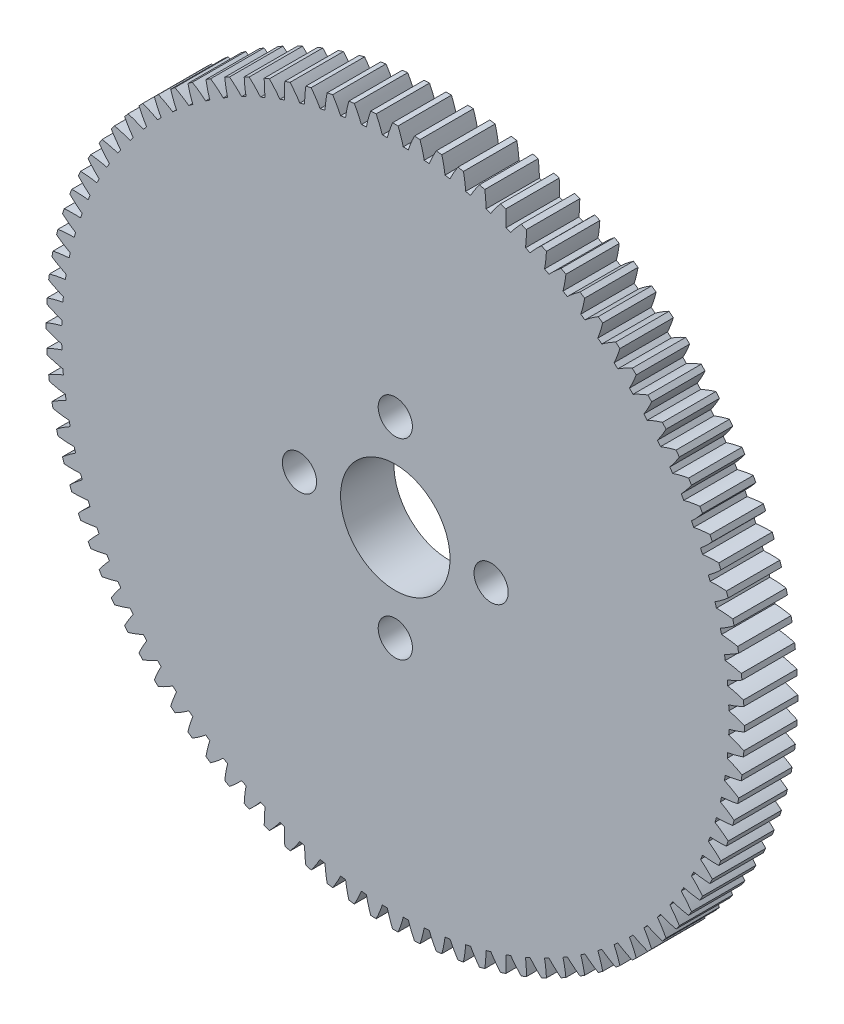
SolidWorks part; units mm, degrees
material "ABS"
ref_plane "Front Plane" through (0, 0, 0) normal (0, 0, 1) x (1, 0, 0)
ref_plane "Top Plane" through (0, 0, 0) normal (0, 1, 0) x (1, 0, 0)
ref_plane "Right Plane" through (0, 0, 0) normal (1, 0, 0) x (0, 0, -1)
ref_plane "Plane1" through (0, 0, 4) normal (0, 0, 1) x (1, 0, 0)
sketch "Sketch1" plane through (0, 0, 4) normal (0, 0, 1) x (1, 0, 0)
  line L0 (25.4992, -0.2018) -> (25.4992, 0.2018)
  line L1 (25.4616, 1.3997) -> (25.4362, 1.8025)
  line L2 (25.3234, 2.9957) -> (25.2728, 3.3961)
  line L3 (25.0854, 4.5799) -> (25.0097, 4.9763)
  line L4 (24.7483, 6.1459) -> (24.6479, 6.5369)
  line L5 (24.3135, 7.6878) -> (24.1888, 8.0716)
  line L6 (23.7828, 9.1993) -> (23.6343, 9.5745)
  line L7 (23.1583, 10.6744) -> (22.9864, 11.0396)
  line L8 (22.4423, 12.1075) -> (22.2479, 12.4612)
  line L9 (21.6378, 13.4928) -> (21.4216, 13.8335)
  line L10 (20.7479, 14.8248) -> (20.5107, 15.1513)
  line L11 (19.7761, 16.0983) -> (19.5188, 16.4093)
  line L12 (18.7263, 17.3083) -> (18.45, 17.6025)
  line L13 (17.6025, 18.45) -> (17.3083, 18.7263)
  line L14 (16.4093, 19.5188) -> (16.0983, 19.7761)
  line L15 (15.1513, 20.5107) -> (14.8248, 20.7479)
  line L16 (13.8335, 21.4216) -> (13.4928, 21.6378)
  line L17 (12.4612, 22.2479) -> (12.1075, 22.4423)
  line L18 (11.0396, 22.9864) -> (10.6744, 23.1583)
  line L19 (9.5745, 23.6343) -> (9.1993, 23.7828)
  line L20 (8.0716, 24.1888) -> (7.6878, 24.3135)
  line L21 (6.5369, 24.6479) -> (6.1459, 24.7483)
  line L22 (4.9763, 25.0097) -> (4.5799, 25.0854)
  line L23 (3.3961, 25.2728) -> (2.9957, 25.3234)
  line L24 (1.8025, 25.4362) -> (1.3997, 25.4616)
  line L25 (0.2018, 25.4992) -> (-0.2018, 25.4992)
  line L26 (-1.3997, 25.4616) -> (-1.8025, 25.4362)
  line L27 (-2.9957, 25.3234) -> (-3.3961, 25.2728)
  line L28 (-4.5799, 25.0854) -> (-4.9763, 25.0097)
  line L29 (-6.1459, 24.7483) -> (-6.5369, 24.6479)
  line L30 (-7.6878, 24.3135) -> (-8.0716, 24.1888)
  line L31 (-9.1993, 23.7828) -> (-9.5745, 23.6343)
  line L32 (-10.6744, 23.1583) -> (-11.0396, 22.9864)
  line L33 (-12.1075, 22.4423) -> (-12.4612, 22.2479)
  line L34 (-13.4928, 21.6378) -> (-13.8335, 21.4216)
  line L35 (-14.8248, 20.7479) -> (-15.1513, 20.5107)
  line L36 (-16.0983, 19.7761) -> (-16.4093, 19.5188)
  line L37 (-17.3083, 18.7263) -> (-17.6025, 18.45)
  line L38 (-18.45, 17.6025) -> (-18.7263, 17.3083)
  line L39 (-19.5188, 16.4093) -> (-19.7761, 16.0983)
  line L40 (-20.5107, 15.1513) -> (-20.7479, 14.8248)
  line L41 (-21.4216, 13.8335) -> (-21.6378, 13.4928)
  line L42 (-22.2479, 12.4612) -> (-22.4423, 12.1075)
  line L43 (-22.9864, 11.0396) -> (-23.1583, 10.6744)
  line L44 (-23.6343, 9.5745) -> (-23.7828, 9.1993)
  line L45 (-24.1888, 8.0716) -> (-24.3135, 7.6878)
  line L46 (-24.6479, 6.5369) -> (-24.7483, 6.1459)
  line L47 (-25.0097, 4.9763) -> (-25.0854, 4.5799)
  line L48 (-25.2728, 3.3961) -> (-25.3234, 2.9957)
  line L49 (-25.4362, 1.8025) -> (-25.4616, 1.3997)
  line L50 (-25.4992, 0.2018) -> (-25.4992, -0.2018)
  line L51 (-25.4616, -1.3997) -> (-25.4362, -1.8025)
  line L52 (-25.3234, -2.9957) -> (-25.2728, -3.3961)
  line L53 (-25.0854, -4.5799) -> (-25.0097, -4.9763)
  line L54 (-24.7483, -6.1459) -> (-24.6479, -6.5369)
  line L55 (-24.3135, -7.6878) -> (-24.1888, -8.0716)
  line L56 (-23.7828, -9.1993) -> (-23.6343, -9.5745)
  line L57 (-23.1583, -10.6744) -> (-22.9864, -11.0396)
  line L58 (-22.4423, -12.1075) -> (-22.2479, -12.4612)
  line L59 (-21.6378, -13.4928) -> (-21.4216, -13.8335)
  line L60 (-20.7479, -14.8248) -> (-20.5107, -15.1513)
  line L61 (-19.7761, -16.0983) -> (-19.5188, -16.4093)
  line L62 (-18.7263, -17.3083) -> (-18.45, -17.6025)
  line L63 (-17.6025, -18.45) -> (-17.3083, -18.7263)
  line L64 (-16.4093, -19.5188) -> (-16.0983, -19.7761)
  line L65 (-15.1513, -20.5107) -> (-14.8248, -20.7479)
  line L66 (-13.8335, -21.4216) -> (-13.4928, -21.6378)
  line L67 (-12.4612, -22.2479) -> (-12.1075, -22.4423)
  line L68 (-11.0396, -22.9864) -> (-10.6744, -23.1583)
  line L69 (-9.5745, -23.6343) -> (-9.1993, -23.7828)
  line L70 (-8.0716, -24.1888) -> (-7.6878, -24.3135)
  line L71 (-6.5369, -24.6479) -> (-6.1459, -24.7483)
  line L72 (-4.9763, -25.0097) -> (-4.5799, -25.0854)
  line L73 (-3.3961, -25.2728) -> (-2.9957, -25.3234)
  line L74 (-1.8025, -25.4362) -> (-1.3997, -25.4616)
  line L75 (-0.2018, -25.4992) -> (0.2018, -25.4992)
  line L76 (1.3997, -25.4616) -> (1.8025, -25.4362)
  line L77 (2.9957, -25.3234) -> (3.3961, -25.2728)
  line L78 (4.5799, -25.0854) -> (4.9763, -25.0097)
  line L79 (6.1459, -24.7483) -> (6.5369, -24.6479)
  line L80 (7.6878, -24.3135) -> (8.0716, -24.1888)
  line L81 (9.1993, -23.7828) -> (9.5745, -23.6343)
  line L82 (10.6744, -23.1583) -> (11.0396, -22.9864)
  line L83 (12.1075, -22.4423) -> (12.4612, -22.2479)
  line L84 (13.4928, -21.6378) -> (13.8335, -21.4216)
  line L85 (14.8248, -20.7479) -> (15.1513, -20.5107)
  line L86 (16.0983, -19.7761) -> (16.4093, -19.5188)
  line L87 (17.3083, -18.7263) -> (17.6025, -18.45)
  line L88 (18.45, -17.6025) -> (18.7263, -17.3083)
  line L89 (19.5188, -16.4093) -> (19.7761, -16.0983)
  line L90 (20.5107, -15.1513) -> (20.7479, -14.8248)
  line L91 (21.4216, -13.8335) -> (21.6378, -13.4928)
  line L92 (22.2479, -12.4612) -> (22.4423, -12.1075)
  line L93 (22.9864, -11.0396) -> (23.1583, -10.6744)
  line L94 (23.6343, -9.5745) -> (23.7828, -9.1993)
  line L95 (24.1888, -8.0716) -> (24.3135, -7.6878)
  line L96 (24.6479, -6.5369) -> (24.7483, -6.1459)
  line L97 (25.0097, -4.9763) -> (25.0854, -4.5799)
  line L98 (25.2728, -3.3961) -> (25.3234, -2.9957)
  line L99 (25.4362, -1.8025) -> (25.4616, -1.3997)
  arc A0 (24.3565, -0.9497) -> (24.3681, -0.5815) centre (0, 0) ccw
  arc A1 (24.3681, -0.5815) -> (25.4992, -0.2018) centre (22.3084, 7.4288) ccw
  arc A2 (25.4992, 0.2018) -> (24.3681, 0.5815) centre (22.3272, -7.3729) ccw
  arc A3 (24.3681, 0.5815) -> (24.3565, 0.9497) centre (0, 0) ccw
  arc A4 (24.3565, 0.9497) -> (25.4616, 1.3997) centre (21.7979, 8.8149) ccw
  arc A5 (25.4362, 1.8025) -> (24.2835, 2.1104) centre (22.7461, -5.9564) ccw
  arc A6 (24.2835, 2.1104) -> (24.2488, 2.4772) centre (0, 0) ccw
  arc A7 (24.2488, 2.4772) -> (25.3234, 2.9957) centre (21.2014, 10.1662) ccw
  arc A8 (25.2728, 3.3961) -> (24.103, 3.631) centre (23.0752, -4.5164) ccw
  arc A9 (24.103, 3.631) -> (24.0454, 3.9949) centre (0, 0) ccw
  arc A10 (24.0454, 3.9949) -> (25.0854, 4.5799) centre (20.5213, 11.4774) ccw
  arc A11 (25.0097, 4.9763) -> (23.8275, 5.1373) centre (23.3132, -3.0586) ccw
  arc A12 (23.8275, 5.1373) -> (23.7471, 5.4969) centre (0, 0) ccw
  arc A13 (23.7471, 5.4969) -> (24.7483, 6.1459) centre (19.7601, 12.7433) ccw
  arc A14 (24.6479, 6.5369) -> (23.4579, 6.6233) centre (23.4593, -1.5887) ccw
  arc A15 (23.4579, 6.6233) -> (23.3551, 6.9771) centre (0, 0) ccw
  arc A16 (23.3551, 6.9771) -> (24.3135, 7.6878) centre (18.921, 13.9589) ccw
  arc A17 (24.1888, 8.0716) -> (22.9957, 8.0832) centre (23.5128, -0.1125) ccw
  arc A18 (22.9957, 8.0832) -> (22.8709, 8.4298) centre (0, 0) ccw
  arc A19 (22.8709, 8.4298) -> (23.7828, 9.1993) centre (18.0071, 15.1194) ccw
  arc A20 (23.6343, 9.5745) -> (22.4428, 9.5112) centre (23.4734, 1.3641) ccw
  arc A21 (22.4428, 9.5112) -> (22.2965, 9.8493) centre (0, 0) ccw
  arc A22 (22.2965, 9.8493) -> (23.1583, 10.6744) centre (17.0222, 16.2202) ccw
  arc A23 (22.9864, 11.0396) -> (21.8013, 10.9016) centre (23.3415, 2.8353) ccw
  arc A24 (21.8013, 10.9016) -> (21.634, 11.2298) centre (0, 0) ccw
  arc A25 (21.634, 11.2298) -> (22.4423, 12.1075) centre (15.9702, 17.257) ccw
  arc A26 (22.2479, 12.4612) -> (21.0738, 12.249) centre (23.1174, 4.2953) ccw
  arc A27 (21.0738, 12.249) -> (20.8862, 12.5661) centre (0, 0) ccw
  arc A28 (20.8862, 12.5661) -> (21.6378, 13.4928) centre (14.8551, 18.2258) ccw
  arc A29 (21.4216, 13.8335) -> (20.263, 13.548) centre (22.8021, 5.7384) ccw
  arc A30 (20.263, 13.548) -> (20.056, 13.8527) centre (0, 0) ccw
  arc A31 (20.056, 13.8527) -> (20.7479, 14.8248) centre (13.6814, 19.1226) ccw
  arc A32 (20.5107, 15.1513) -> (19.3724, 14.7936) centre (22.3967, 7.1588) ccw
  arc A33 (19.3724, 14.7936) -> (19.1466, 15.0847) centre (0, 0) ccw
  arc A34 (19.1466, 15.0847) -> (19.7761, 16.0983) centre (12.4537, 19.9439) ccw
  arc A35 (19.5188, 16.4093) -> (18.4052, 15.9808) centre (21.903, 8.551) ccw
  arc A36 (18.4052, 15.9808) -> (18.1616, 16.2572) centre (0, 0) ccw
  arc A37 (18.1616, 16.2572) -> (18.7263, 17.3083) centre (11.1768, 20.6865) ccw
  arc A38 (18.45, 17.6025) -> (17.3655, 17.105) centre (21.3229, 9.9094) ccw
  arc A39 (17.3655, 17.105) -> (17.105, 17.3655) centre (0, 0) ccw
  arc A40 (17.105, 17.3655) -> (17.6025, 18.45) centre (9.8558, 21.3475) ccw
  arc A41 (17.3083, 18.7263) -> (16.2572, 18.1616) centre (20.6586, 11.2287) ccw
  arc A42 (16.2572, 18.1616) -> (15.9808, 18.4052) centre (0, 0) ccw
  arc A43 (15.9808, 18.4052) -> (16.4093, 19.5188) centre (8.496, 21.9242) ccw
  arc A44 (16.0983, 19.7761) -> (15.0847, 19.1466) centre (19.9128, 12.5037) ccw
  arc A45 (15.0847, 19.1466) -> (14.7936, 19.3724) centre (0, 0) ccw
  arc A46 (14.7936, 19.3724) -> (15.1513, 20.5107) centre (7.1026, 22.4144) ccw
  arc A47 (14.8248, 20.7479) -> (13.8527, 20.056) centre (19.0884, 13.7294) ccw
  arc A48 (13.8527, 20.056) -> (13.548, 20.263) centre (0, 0) ccw
  arc A49 (13.548, 20.263) -> (13.8335, 21.4216) centre (5.6811, 22.8162) ccw
  arc A50 (13.4928, 21.6378) -> (12.5661, 20.8862) centre (18.1886, 14.9009) ccw
  arc A51 (12.5661, 20.8862) -> (12.249, 21.0738) centre (0, 0) ccw
  arc A52 (12.249, 21.0738) -> (12.4612, 22.2479) centre (4.2373, 23.1279) ccw
  arc A53 (12.1075, 22.4423) -> (11.2298, 21.634) centre (17.2171, 16.0136) ccw
  arc A54 (11.2298, 21.634) -> (10.9016, 21.8013) centre (0, 0) ccw
  arc A55 (10.9016, 21.8013) -> (11.0396, 22.9864) centre (2.7767, 23.3483) ccw
  arc A56 (10.6744, 23.1583) -> (9.8493, 22.2965) centre (16.1776, 17.063) ccw
  arc A57 (9.8493, 22.2965) -> (9.5112, 22.4428) centre (0, 0) ccw
  arc A58 (9.5112, 22.4428) -> (9.5745, 23.6343) centre (1.3052, 23.4766) ccw
  arc A59 (9.1993, 23.7828) -> (8.4298, 22.8709) centre (15.0743, 18.0452) ccw
  arc A60 (8.4298, 22.8709) -> (8.0832, 22.9957) centre (0, 0) ccw
  arc A61 (8.0832, 22.9957) -> (8.0716, 24.1888) centre (-0.1715, 23.5122) ccw
  arc A62 (7.6878, 24.3135) -> (6.9771, 23.3551) centre (13.9115, 18.9561) ccw
  arc A63 (6.9771, 23.3551) -> (6.6233, 23.4579) centre (0, 0) ccw
  arc A64 (6.6233, 23.4579) -> (6.5369, 24.6479) centre (-1.6475, 23.455) ccw
  arc A65 (6.1459, 24.7483) -> (5.4969, 23.7471) centre (12.6938, 19.7922) ccw
  arc A66 (5.4969, 23.7471) -> (5.1373, 23.8275) centre (0, 0) ccw
  arc A67 (5.1373, 23.8275) -> (4.9763, 25.0097) centre (-3.117, 23.3053) ccw
  arc A68 (4.5799, 25.0854) -> (3.9949, 24.0454) centre (11.426, 20.5502) ccw
  arc A69 (3.9949, 24.0454) -> (3.631, 24.103) centre (0, 0) ccw
  arc A70 (3.631, 24.103) -> (3.3961, 25.2728) centre (-4.5742, 23.0636) ccw
  arc A71 (2.9957, 25.3234) -> (2.4772, 24.2488) centre (10.1131, 21.2271) ccw
  arc A72 (2.4772, 24.2488) -> (2.1104, 24.2835) centre (0, 0) ccw
  arc A73 (2.1104, 24.2835) -> (1.8025, 25.4362) centre (-6.0134, 22.7309) ccw
  arc A74 (1.3997, 25.4616) -> (0.9497, 24.3565) centre (8.7603, 21.8202) ccw
  arc A75 (0.9497, 24.3565) -> (0.5815, 24.3681) centre (0, 0) ccw
  arc A76 (0.5815, 24.3681) -> (0.2018, 25.4992) centre (-7.4288, 22.3084) ccw
  arc A77 (-0.2018, 25.4992) -> (-0.5815, 24.3681) centre (7.3729, 22.3272) ccw
  arc A78 (-0.5815, 24.3681) -> (-0.9497, 24.3565) centre (0, 0) ccw
  arc A79 (-0.9497, 24.3565) -> (-1.3997, 25.4616) centre (-8.8149, 21.7979) ccw
  arc A80 (-1.8025, 25.4362) -> (-2.1104, 24.2835) centre (5.9564, 22.7461) ccw
  arc A81 (-2.1104, 24.2835) -> (-2.4772, 24.2488) centre (0, 0) ccw
  arc A82 (-2.4772, 24.2488) -> (-2.9957, 25.3234) centre (-10.1662, 21.2014) ccw
  arc A83 (-3.3961, 25.2728) -> (-3.631, 24.103) centre (4.5164, 23.0752) ccw
  arc A84 (-3.631, 24.103) -> (-3.9949, 24.0454) centre (0, 0) ccw
  arc A85 (-3.9949, 24.0454) -> (-4.5799, 25.0854) centre (-11.4774, 20.5213) ccw
  arc A86 (-4.9763, 25.0097) -> (-5.1373, 23.8275) centre (3.0586, 23.3132) ccw
  arc A87 (-5.1373, 23.8275) -> (-5.4969, 23.7471) centre (0, 0) ccw
  arc A88 (-5.4969, 23.7471) -> (-6.1459, 24.7483) centre (-12.7433, 19.7601) ccw
  arc A89 (-6.5369, 24.6479) -> (-6.6233, 23.4579) centre (1.5887, 23.4593) ccw
  arc A90 (-6.6233, 23.4579) -> (-6.9771, 23.3551) centre (0, 0) ccw
  arc A91 (-6.9771, 23.3551) -> (-7.6878, 24.3135) centre (-13.9589, 18.921) ccw
  arc A92 (-8.0716, 24.1888) -> (-8.0832, 22.9957) centre (0.1125, 23.5128) ccw
  arc A93 (-8.0832, 22.9957) -> (-8.4298, 22.8709) centre (0, 0) ccw
  arc A94 (-8.4298, 22.8709) -> (-9.1993, 23.7828) centre (-15.1194, 18.0071) ccw
  arc A95 (-9.5745, 23.6343) -> (-9.5112, 22.4428) centre (-1.3641, 23.4734) ccw
  arc A96 (-9.5112, 22.4428) -> (-9.8493, 22.2965) centre (0, 0) ccw
  arc A97 (-9.8493, 22.2965) -> (-10.6744, 23.1583) centre (-16.2202, 17.0222) ccw
  arc A98 (-11.0396, 22.9864) -> (-10.9016, 21.8013) centre (-2.8353, 23.3415) ccw
  arc A99 (-10.9016, 21.8013) -> (-11.2298, 21.634) centre (0, 0) ccw
  arc A100 (-11.2298, 21.634) -> (-12.1075, 22.4423) centre (-17.257, 15.9702) ccw
  arc A101 (-12.4612, 22.2479) -> (-12.249, 21.0738) centre (-4.2953, 23.1174) ccw
  arc A102 (-12.249, 21.0738) -> (-12.5661, 20.8862) centre (0, 0) ccw
  arc A103 (-12.5661, 20.8862) -> (-13.4928, 21.6378) centre (-18.2258, 14.8551) ccw
  arc A104 (-13.8335, 21.4216) -> (-13.548, 20.263) centre (-5.7384, 22.8021) ccw
  arc A105 (-13.548, 20.263) -> (-13.8527, 20.056) centre (0, 0) ccw
  arc A106 (-13.8527, 20.056) -> (-14.8248, 20.7479) centre (-19.1226, 13.6814) ccw
  arc A107 (-15.1513, 20.5107) -> (-14.7936, 19.3724) centre (-7.1588, 22.3967) ccw
  arc A108 (-14.7936, 19.3724) -> (-15.0847, 19.1466) centre (0, 0) ccw
  arc A109 (-15.0847, 19.1466) -> (-16.0983, 19.7761) centre (-19.9439, 12.4537) ccw
  arc A110 (-16.4093, 19.5188) -> (-15.9808, 18.4052) centre (-8.551, 21.903) ccw
  arc A111 (-15.9808, 18.4052) -> (-16.2572, 18.1616) centre (0, 0) ccw
  arc A112 (-16.2572, 18.1616) -> (-17.3083, 18.7263) centre (-20.6865, 11.1768) ccw
  arc A113 (-17.6025, 18.45) -> (-17.105, 17.3655) centre (-9.9094, 21.3229) ccw
  arc A114 (-17.105, 17.3655) -> (-17.3655, 17.105) centre (0, 0) ccw
  arc A115 (-17.3655, 17.105) -> (-18.45, 17.6025) centre (-21.3475, 9.8558) ccw
  arc A116 (-18.7263, 17.3083) -> (-18.1616, 16.2572) centre (-11.2287, 20.6586) ccw
  arc A117 (-18.1616, 16.2572) -> (-18.4052, 15.9808) centre (0, 0) ccw
  arc A118 (-18.4052, 15.9808) -> (-19.5188, 16.4093) centre (-21.9242, 8.496) ccw
  arc A119 (-19.7761, 16.0983) -> (-19.1466, 15.0847) centre (-12.5037, 19.9128) ccw
  arc A120 (-19.1466, 15.0847) -> (-19.3724, 14.7936) centre (0, 0) ccw
  arc A121 (-19.3724, 14.7936) -> (-20.5107, 15.1513) centre (-22.4144, 7.1026) ccw
  arc A122 (-20.7479, 14.8248) -> (-20.056, 13.8527) centre (-13.7294, 19.0884) ccw
  arc A123 (-20.056, 13.8527) -> (-20.263, 13.548) centre (0, 0) ccw
  arc A124 (-20.263, 13.548) -> (-21.4216, 13.8335) centre (-22.8162, 5.6811) ccw
  arc A125 (-21.6378, 13.4928) -> (-20.8862, 12.5661) centre (-14.9009, 18.1886) ccw
  arc A126 (-20.8862, 12.5661) -> (-21.0738, 12.249) centre (0, 0) ccw
  arc A127 (-21.0738, 12.249) -> (-22.2479, 12.4612) centre (-23.1279, 4.2373) ccw
  arc A128 (-22.4423, 12.1075) -> (-21.634, 11.2298) centre (-16.0136, 17.2171) ccw
  arc A129 (-21.634, 11.2298) -> (-21.8013, 10.9016) centre (0, 0) ccw
  arc A130 (-21.8013, 10.9016) -> (-22.9864, 11.0396) centre (-23.3483, 2.7767) ccw
  arc A131 (-23.1583, 10.6744) -> (-22.2965, 9.8493) centre (-17.063, 16.1776) ccw
  arc A132 (-22.2965, 9.8493) -> (-22.4428, 9.5112) centre (0, 0) ccw
  arc A133 (-22.4428, 9.5112) -> (-23.6343, 9.5745) centre (-23.4766, 1.3052) ccw
  arc A134 (-23.7828, 9.1993) -> (-22.8709, 8.4298) centre (-18.0452, 15.0743) ccw
  arc A135 (-22.8709, 8.4298) -> (-22.9957, 8.0832) centre (0, 0) ccw
  arc A136 (-22.9957, 8.0832) -> (-24.1888, 8.0716) centre (-23.5122, -0.1715) ccw
  arc A137 (-24.3135, 7.6878) -> (-23.3551, 6.9771) centre (-18.9561, 13.9115) ccw
  arc A138 (-23.3551, 6.9771) -> (-23.4579, 6.6233) centre (0, 0) ccw
  arc A139 (-23.4579, 6.6233) -> (-24.6479, 6.5369) centre (-23.455, -1.6475) ccw
  arc A140 (-24.7483, 6.1459) -> (-23.7471, 5.4969) centre (-19.7922, 12.6938) ccw
  arc A141 (-23.7471, 5.4969) -> (-23.8275, 5.1373) centre (0, 0) ccw
  arc A142 (-23.8275, 5.1373) -> (-25.0097, 4.9763) centre (-23.3053, -3.117) ccw
  arc A143 (-25.0854, 4.5799) -> (-24.0454, 3.9949) centre (-20.5502, 11.426) ccw
  arc A144 (-24.0454, 3.9949) -> (-24.103, 3.631) centre (0, 0) ccw
  arc A145 (-24.103, 3.631) -> (-25.2728, 3.3961) centre (-23.0636, -4.5742) ccw
  arc A146 (-25.3234, 2.9957) -> (-24.2488, 2.4772) centre (-21.2271, 10.1131) ccw
  arc A147 (-24.2488, 2.4772) -> (-24.2835, 2.1104) centre (0, 0) ccw
  arc A148 (-24.2835, 2.1104) -> (-25.4362, 1.8025) centre (-22.7309, -6.0134) ccw
  arc A149 (-25.4616, 1.3997) -> (-24.3565, 0.9497) centre (-21.8202, 8.7603) ccw
  arc A150 (-24.3565, 0.9497) -> (-24.3681, 0.5815) centre (0, 0) ccw
  arc A151 (-24.3681, 0.5815) -> (-25.4992, 0.2018) centre (-22.3084, -7.4288) ccw
  arc A152 (-25.4992, -0.2018) -> (-24.3681, -0.5815) centre (-22.3272, 7.3729) ccw
  arc A153 (-24.3681, -0.5815) -> (-24.3565, -0.9497) centre (0, 0) ccw
  arc A154 (-24.3565, -0.9497) -> (-25.4616, -1.3997) centre (-21.7979, -8.8149) ccw
  arc A155 (-25.4362, -1.8025) -> (-24.2835, -2.1104) centre (-22.7461, 5.9564) ccw
  arc A156 (-24.2835, -2.1104) -> (-24.2488, -2.4772) centre (0, 0) ccw
  arc A157 (-24.2488, -2.4772) -> (-25.3234, -2.9957) centre (-21.2014, -10.1662) ccw
  arc A158 (-25.2728, -3.3961) -> (-24.103, -3.631) centre (-23.0752, 4.5164) ccw
  arc A159 (-24.103, -3.631) -> (-24.0454, -3.9949) centre (0, 0) ccw
  arc A160 (-24.0454, -3.9949) -> (-25.0854, -4.5799) centre (-20.5213, -11.4774) ccw
  arc A161 (-25.0097, -4.9763) -> (-23.8275, -5.1373) centre (-23.3132, 3.0586) ccw
  arc A162 (-23.8275, -5.1373) -> (-23.7471, -5.4969) centre (0, 0) ccw
  arc A163 (-23.7471, -5.4969) -> (-24.7483, -6.1459) centre (-19.7601, -12.7433) ccw
  arc A164 (-24.6479, -6.5369) -> (-23.4579, -6.6233) centre (-23.4593, 1.5887) ccw
  arc A165 (-23.4579, -6.6233) -> (-23.3551, -6.9771) centre (0, 0) ccw
  arc A166 (-23.3551, -6.9771) -> (-24.3135, -7.6878) centre (-18.921, -13.9589) ccw
  arc A167 (-24.1888, -8.0716) -> (-22.9957, -8.0832) centre (-23.5128, 0.1125) ccw
  arc A168 (-22.9957, -8.0832) -> (-22.8709, -8.4298) centre (0, 0) ccw
  arc A169 (-22.8709, -8.4298) -> (-23.7828, -9.1993) centre (-18.0071, -15.1194) ccw
  arc A170 (-23.6343, -9.5745) -> (-22.4428, -9.5112) centre (-23.4734, -1.3641) ccw
  arc A171 (-22.4428, -9.5112) -> (-22.2965, -9.8493) centre (0, 0) ccw
  arc A172 (-22.2965, -9.8493) -> (-23.1583, -10.6744) centre (-17.0222, -16.2202) ccw
  arc A173 (-22.9864, -11.0396) -> (-21.8013, -10.9016) centre (-23.3415, -2.8353) ccw
  arc A174 (-21.8013, -10.9016) -> (-21.634, -11.2298) centre (0, 0) ccw
  arc A175 (-21.634, -11.2298) -> (-22.4423, -12.1075) centre (-15.9702, -17.257) ccw
  arc A176 (-22.2479, -12.4612) -> (-21.0738, -12.249) centre (-23.1174, -4.2953) ccw
  arc A177 (-21.0738, -12.249) -> (-20.8862, -12.5661) centre (0, 0) ccw
  arc A178 (-20.8862, -12.5661) -> (-21.6378, -13.4928) centre (-14.8551, -18.2258) ccw
  arc A179 (-21.4216, -13.8335) -> (-20.263, -13.548) centre (-22.8021, -5.7384) ccw
  arc A180 (-20.263, -13.548) -> (-20.056, -13.8527) centre (0, 0) ccw
  arc A181 (-20.056, -13.8527) -> (-20.7479, -14.8248) centre (-13.6814, -19.1226) ccw
  arc A182 (-20.5107, -15.1513) -> (-19.3724, -14.7936) centre (-22.3967, -7.1588) ccw
  arc A183 (-19.3724, -14.7936) -> (-19.1466, -15.0847) centre (0, 0) ccw
  arc A184 (-19.1466, -15.0847) -> (-19.7761, -16.0983) centre (-12.4537, -19.9439) ccw
  arc A185 (-19.5188, -16.4093) -> (-18.4052, -15.9808) centre (-21.903, -8.551) ccw
  arc A186 (-18.4052, -15.9808) -> (-18.1616, -16.2572) centre (0, 0) ccw
  arc A187 (-18.1616, -16.2572) -> (-18.7263, -17.3083) centre (-11.1768, -20.6865) ccw
  arc A188 (-18.45, -17.6025) -> (-17.3655, -17.105) centre (-21.3229, -9.9094) ccw
  arc A189 (-17.3655, -17.105) -> (-17.105, -17.3655) centre (0, 0) ccw
  arc A190 (-17.105, -17.3655) -> (-17.6025, -18.45) centre (-9.8558, -21.3475) ccw
  arc A191 (-17.3083, -18.7263) -> (-16.2572, -18.1616) centre (-20.6586, -11.2287) ccw
  arc A192 (-16.2572, -18.1616) -> (-15.9808, -18.4052) centre (0, 0) ccw
  arc A193 (-15.9808, -18.4052) -> (-16.4093, -19.5188) centre (-8.496, -21.9242) ccw
  arc A194 (-16.0983, -19.7761) -> (-15.0847, -19.1466) centre (-19.9128, -12.5037) ccw
  arc A195 (-15.0847, -19.1466) -> (-14.7936, -19.3724) centre (0, 0) ccw
  arc A196 (-14.7936, -19.3724) -> (-15.1513, -20.5107) centre (-7.1026, -22.4144) ccw
  arc A197 (-14.8248, -20.7479) -> (-13.8527, -20.056) centre (-19.0884, -13.7294) ccw
  arc A198 (-13.8527, -20.056) -> (-13.548, -20.263) centre (0, 0) ccw
  arc A199 (-13.548, -20.263) -> (-13.8335, -21.4216) centre (-5.6811, -22.8162) ccw
  arc A200 (-13.4928, -21.6378) -> (-12.5661, -20.8862) centre (-18.1886, -14.9009) ccw
  arc A201 (-12.5661, -20.8862) -> (-12.249, -21.0738) centre (0, 0) ccw
  arc A202 (-12.249, -21.0738) -> (-12.4612, -22.2479) centre (-4.2373, -23.1279) ccw
  arc A203 (-12.1075, -22.4423) -> (-11.2298, -21.634) centre (-17.2171, -16.0136) ccw
  arc A204 (-11.2298, -21.634) -> (-10.9016, -21.8013) centre (0, 0) ccw
  arc A205 (-10.9016, -21.8013) -> (-11.0396, -22.9864) centre (-2.7767, -23.3483) ccw
  arc A206 (-10.6744, -23.1583) -> (-9.8493, -22.2965) centre (-16.1776, -17.063) ccw
  arc A207 (-9.8493, -22.2965) -> (-9.5112, -22.4428) centre (0, 0) ccw
  arc A208 (-9.5112, -22.4428) -> (-9.5745, -23.6343) centre (-1.3052, -23.4766) ccw
  arc A209 (-9.1993, -23.7828) -> (-8.4298, -22.8709) centre (-15.0743, -18.0452) ccw
  arc A210 (-8.4298, -22.8709) -> (-8.0832, -22.9957) centre (0, 0) ccw
  arc A211 (-8.0832, -22.9957) -> (-8.0716, -24.1888) centre (0.1715, -23.5122) ccw
  arc A212 (-7.6878, -24.3135) -> (-6.9771, -23.3551) centre (-13.9115, -18.9561) ccw
  arc A213 (-6.9771, -23.3551) -> (-6.6233, -23.4579) centre (0, 0) ccw
  arc A214 (-6.6233, -23.4579) -> (-6.5369, -24.6479) centre (1.6475, -23.455) ccw
  arc A215 (-6.1459, -24.7483) -> (-5.4969, -23.7471) centre (-12.6938, -19.7922) ccw
  arc A216 (-5.4969, -23.7471) -> (-5.1373, -23.8275) centre (0, 0) ccw
  arc A217 (-5.1373, -23.8275) -> (-4.9763, -25.0097) centre (3.117, -23.3053) ccw
  arc A218 (-4.5799, -25.0854) -> (-3.9949, -24.0454) centre (-11.426, -20.5502) ccw
  arc A219 (-3.9949, -24.0454) -> (-3.631, -24.103) centre (0, 0) ccw
  arc A220 (-3.631, -24.103) -> (-3.3961, -25.2728) centre (4.5742, -23.0636) ccw
  arc A221 (-2.9957, -25.3234) -> (-2.4772, -24.2488) centre (-10.1131, -21.2271) ccw
  arc A222 (-2.4772, -24.2488) -> (-2.1104, -24.2835) centre (0, 0) ccw
  arc A223 (-2.1104, -24.2835) -> (-1.8025, -25.4362) centre (6.0134, -22.7309) ccw
  arc A224 (-1.3997, -25.4616) -> (-0.9497, -24.3565) centre (-8.7603, -21.8202) ccw
  arc A225 (-0.9497, -24.3565) -> (-0.5815, -24.3681) centre (0, 0) ccw
  arc A226 (-0.5815, -24.3681) -> (-0.2018, -25.4992) centre (7.4288, -22.3084) ccw
  arc A227 (0.2018, -25.4992) -> (0.5815, -24.3681) centre (-7.3729, -22.3272) ccw
  arc A228 (0.5815, -24.3681) -> (0.9497, -24.3565) centre (0, 0) ccw
  arc A229 (0.9497, -24.3565) -> (1.3997, -25.4616) centre (8.8149, -21.7979) ccw
  arc A230 (1.8025, -25.4362) -> (2.1104, -24.2835) centre (-5.9564, -22.7461) ccw
  arc A231 (2.1104, -24.2835) -> (2.4772, -24.2488) centre (0, 0) ccw
  arc A232 (2.4772, -24.2488) -> (2.9957, -25.3234) centre (10.1662, -21.2014) ccw
  arc A233 (3.3961, -25.2728) -> (3.631, -24.103) centre (-4.5164, -23.0752) ccw
  arc A234 (3.631, -24.103) -> (3.9949, -24.0454) centre (0, 0) ccw
  arc A235 (3.9949, -24.0454) -> (4.5799, -25.0854) centre (11.4774, -20.5213) ccw
  arc A236 (4.9763, -25.0097) -> (5.1373, -23.8275) centre (-3.0586, -23.3132) ccw
  arc A237 (5.1373, -23.8275) -> (5.4969, -23.7471) centre (0, 0) ccw
  arc A238 (5.4969, -23.7471) -> (6.1459, -24.7483) centre (12.7433, -19.7601) ccw
  arc A239 (6.5369, -24.6479) -> (6.6233, -23.4579) centre (-1.5887, -23.4593) ccw
  arc A240 (6.6233, -23.4579) -> (6.9771, -23.3551) centre (0, 0) ccw
  arc A241 (6.9771, -23.3551) -> (7.6878, -24.3135) centre (13.9589, -18.921) ccw
  arc A242 (8.0716, -24.1888) -> (8.0832, -22.9957) centre (-0.1125, -23.5128) ccw
  arc A243 (8.0832, -22.9957) -> (8.4298, -22.8709) centre (0, 0) ccw
  arc A244 (8.4298, -22.8709) -> (9.1993, -23.7828) centre (15.1194, -18.0071) ccw
  arc A245 (9.5745, -23.6343) -> (9.5112, -22.4428) centre (1.3641, -23.4734) ccw
  arc A246 (9.5112, -22.4428) -> (9.8493, -22.2965) centre (0, 0) ccw
  arc A247 (9.8493, -22.2965) -> (10.6744, -23.1583) centre (16.2202, -17.0222) ccw
  arc A248 (11.0396, -22.9864) -> (10.9016, -21.8013) centre (2.8353, -23.3415) ccw
  arc A249 (10.9016, -21.8013) -> (11.2298, -21.634) centre (0, 0) ccw
  arc A250 (11.2298, -21.634) -> (12.1075, -22.4423) centre (17.257, -15.9702) ccw
  arc A251 (12.4612, -22.2479) -> (12.249, -21.0738) centre (4.2953, -23.1174) ccw
  arc A252 (12.249, -21.0738) -> (12.5661, -20.8862) centre (0, 0) ccw
  arc A253 (12.5661, -20.8862) -> (13.4928, -21.6378) centre (18.2258, -14.8551) ccw
  arc A254 (13.8335, -21.4216) -> (13.548, -20.263) centre (5.7384, -22.8021) ccw
  arc A255 (13.548, -20.263) -> (13.8527, -20.056) centre (0, 0) ccw
  arc A256 (13.8527, -20.056) -> (14.8248, -20.7479) centre (19.1226, -13.6814) ccw
  arc A257 (15.1513, -20.5107) -> (14.7936, -19.3724) centre (7.1588, -22.3967) ccw
  arc A258 (14.7936, -19.3724) -> (15.0847, -19.1466) centre (0, 0) ccw
  arc A259 (15.0847, -19.1466) -> (16.0983, -19.7761) centre (19.9439, -12.4537) ccw
  arc A260 (16.4093, -19.5188) -> (15.9808, -18.4052) centre (8.551, -21.903) ccw
  arc A261 (15.9808, -18.4052) -> (16.2572, -18.1616) centre (0, 0) ccw
  arc A262 (16.2572, -18.1616) -> (17.3083, -18.7263) centre (20.6865, -11.1768) ccw
  arc A263 (17.6025, -18.45) -> (17.105, -17.3655) centre (9.9094, -21.3229) ccw
  arc A264 (17.105, -17.3655) -> (17.3655, -17.105) centre (0, 0) ccw
  arc A265 (17.3655, -17.105) -> (18.45, -17.6025) centre (21.3475, -9.8558) ccw
  arc A266 (18.7263, -17.3083) -> (18.1616, -16.2572) centre (11.2287, -20.6586) ccw
  arc A267 (18.1616, -16.2572) -> (18.4052, -15.9808) centre (0, 0) ccw
  arc A268 (18.4052, -15.9808) -> (19.5188, -16.4093) centre (21.9242, -8.496) ccw
  arc A269 (19.7761, -16.0983) -> (19.1466, -15.0847) centre (12.5037, -19.9128) ccw
  arc A270 (19.1466, -15.0847) -> (19.3724, -14.7936) centre (0, 0) ccw
  arc A271 (19.3724, -14.7936) -> (20.5107, -15.1513) centre (22.4144, -7.1026) ccw
  arc A272 (20.7479, -14.8248) -> (20.056, -13.8527) centre (13.7294, -19.0884) ccw
  arc A273 (20.056, -13.8527) -> (20.263, -13.548) centre (0, 0) ccw
  arc A274 (20.263, -13.548) -> (21.4216, -13.8335) centre (22.8162, -5.6811) ccw
  arc A275 (21.6378, -13.4928) -> (20.8862, -12.5661) centre (14.9009, -18.1886) ccw
  arc A276 (20.8862, -12.5661) -> (21.0738, -12.249) centre (0, 0) ccw
  arc A277 (21.0738, -12.249) -> (22.2479, -12.4612) centre (23.1279, -4.2373) ccw
  arc A278 (22.4423, -12.1075) -> (21.634, -11.2298) centre (16.0136, -17.2171) ccw
  arc A279 (21.634, -11.2298) -> (21.8013, -10.9016) centre (0, 0) ccw
  arc A280 (21.8013, -10.9016) -> (22.9864, -11.0396) centre (23.3483, -2.7767) ccw
  arc A281 (23.1583, -10.6744) -> (22.2965, -9.8493) centre (17.063, -16.1776) ccw
  arc A282 (22.2965, -9.8493) -> (22.4428, -9.5112) centre (0, 0) ccw
  arc A283 (22.4428, -9.5112) -> (23.6343, -9.5745) centre (23.4766, -1.3052) ccw
  arc A284 (23.7828, -9.1993) -> (22.8709, -8.4298) centre (18.0452, -15.0743) ccw
  arc A285 (22.8709, -8.4298) -> (22.9957, -8.0832) centre (0, 0) ccw
  arc A286 (22.9957, -8.0832) -> (24.1888, -8.0716) centre (23.5122, 0.1715) ccw
  arc A287 (24.3135, -7.6878) -> (23.3551, -6.9771) centre (18.9561, -13.9115) ccw
  arc A288 (23.3551, -6.9771) -> (23.4579, -6.6233) centre (0, 0) ccw
  arc A289 (23.4579, -6.6233) -> (24.6479, -6.5369) centre (23.455, 1.6475) ccw
  arc A290 (24.7483, -6.1459) -> (23.7471, -5.4969) centre (19.7922, -12.6938) ccw
  arc A291 (23.7471, -5.4969) -> (23.8275, -5.1373) centre (0, 0) ccw
  arc A292 (23.8275, -5.1373) -> (25.0097, -4.9763) centre (23.3053, 3.117) ccw
  arc A293 (25.0854, -4.5799) -> (24.0454, -3.9949) centre (20.5502, -11.426) ccw
  arc A294 (24.0454, -3.9949) -> (24.103, -3.631) centre (0, 0) ccw
  arc A295 (24.103, -3.631) -> (25.2728, -3.3961) centre (23.0636, 4.5742) ccw
  arc A296 (25.3234, -2.9957) -> (24.2488, -2.4772) centre (21.2271, -10.1131) ccw
  arc A297 (24.2488, -2.4772) -> (24.2835, -2.1104) centre (0, 0) ccw
  arc A298 (24.2835, -2.1104) -> (25.4362, -1.8025) centre (22.7309, 6.0134) ccw
  arc A299 (25.4616, -1.3997) -> (24.3565, -0.9497) centre (21.8202, -8.7603) ccw
extrude "Boss-Extrude1" add sketch "Sketch1" against normal blind 3.9
sketch "Sketch2" plane through (0, 0, 4) normal (0, 0, 1) x (1, 0, 0)
  circle A0 centre (0, 0) radius 4
  circle A1 centre (0, 7) radius 1.25
  circle A2 centre (7, 0) radius 1.25
  circle A3 centre (0, -7) radius 1.25
  circle A4 centre (-7, 0) radius 1.25
  point P14 (0, 0)
  dimension "D1" = 8
  dimension "D2" = 2.5
  dimension "D3" = 7
  dimension "D4" = 4
extrude "Cut-Extrude1" cut sketch "Sketch2" against normal through all
